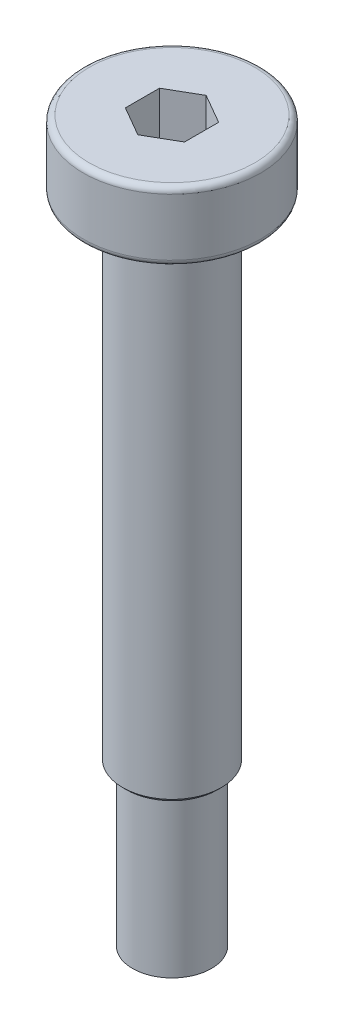
SolidWorks part; units mm, degrees
ref_plane "前视基准面" through (0, 0, 0) normal (0, 0, 1) x (1, 0, 0)
ref_plane "上视基准面" through (0, 0, 0) normal (0, 1, 0) x (1, 0, 0)
ref_plane "右视基准面" through (0, 0, 0) normal (1, 0, 0) x (0, 0, -1)
sketch "草图1" plane through (0, 0, 0) normal (0, 0, 1) x (1, 0, 0)
  line L0 (0, 0) -> (0, -15.0528) construction
  line L1 (0, 0) -> (0, 3.5) construction
  line L2 (0, 3.5) -> (-4.5, 3.5)
  line L3 (-4.5, 3.5) -> (-4.5, 0)
  line L4 (-4.5, 0) -> (-2.5, 0)
  line L5 (-2.5, 0) -> (-2.5, -25)
  line L6 (-2.5, -25) -> (-2, -25)
  line L7 (-2, -25) -> (-2, -33)
  line L8 (-2, -33) -> (0, -33)
  line L9 (0, 3.5) -> (0, -33)
  dimension "D1" = 9
  dimension "D2" = 5
  dimension "D3" = 3.5
  dimension "D4" = 25
  dimension "D5" = 8
  dimension "D6" = 4
revolve "旋转1" add sketch "草图1" angle 360 about L9
cosmetic thread "装饰螺纹线1" parameters "D2"=3.22
fillet "圆角1" radius 0.3 2 edges at (-4.5, 0, 0) (-4.5, 3.5, 0)
sketch "草图2" plane through (0, 3.5, 0) normal (0, 1, 0) x (1, 0, 0)
  line L1 (0, 1.7321) -> (-1.5, 0.866)
  line L2 (-1.5, 0.866) -> (-1.5, -0.866)
  line L3 (-1.5, -0.866) -> (0, -1.7321)
  line L4 (0, -1.7321) -> (1.5, -0.866)
  line L5 (1.5, -0.866) -> (1.5, 0.866)
  line L6 (1.5, 0.866) -> (0, 1.7321)
  circle A0 centre (0, 0) radius 1.5 construction
  dimension "D1" = 3
extrude "切除-拉伸1" cut sketch "草图2" against normal blind 2.4
chamfer "倒角1" distance 0.2 angle 45 1 edges at (-2.5, -25, 0)
